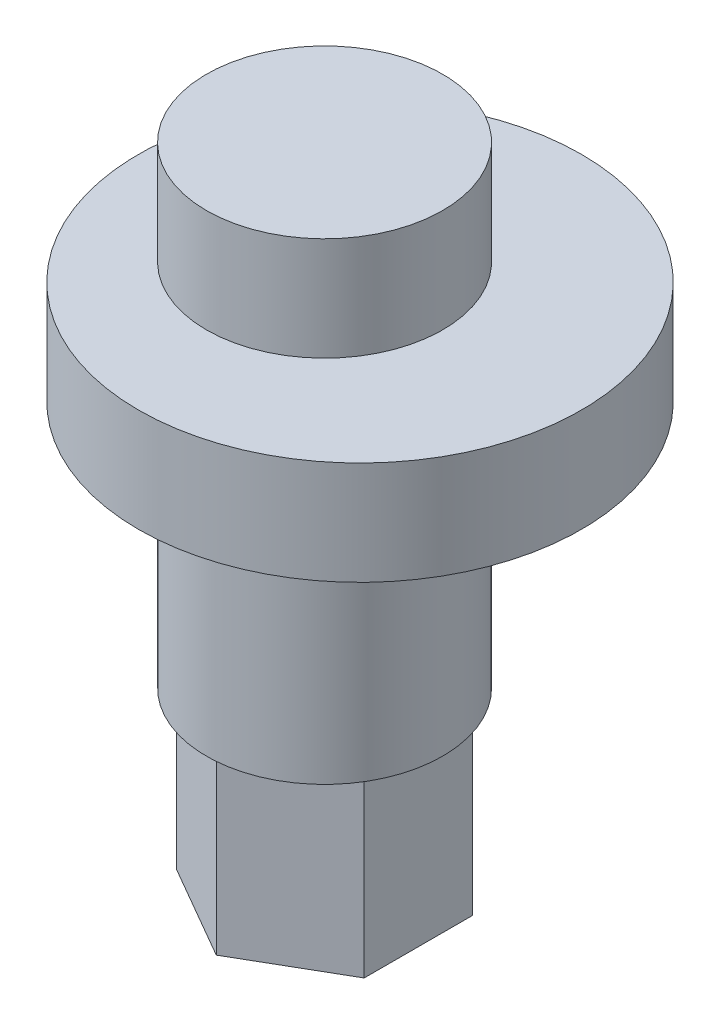
SolidWorks part; units mm, degrees
ref_plane "Front Plane" through (0, 0, 0) normal (0, 0, 1) x (1, 0, 0)
ref_plane "Top Plane" through (0, 0, 0) normal (0, 1, 0) x (1, 0, 0)
ref_plane "Right Plane" through (0, 0, 0) normal (1, 0, 0) x (0, 0, -1)
sketch "Sketch2" plane through (0, 0, 0) normal (0, 1, 0) x (1, 0, 0)
  circle A0 centre (0, 0) radius 4
  circle A1 centre (1.2, 0) radius 7.5
  dimension "D1" = 8
  dimension "D2" = 15
  dimension "D3" = 1.2
sketch "Sketch3" plane through (0, 0, 0) normal (0, 1, 0) x (1, 0, 0)
  circle A0 centre (1.2, 0) radius 7.5 construction
  circle A1 centre (1.2, 0) radius 7.5
extrude "Boss-Extrude1" add sketch "Sketch3" along normal blind 3.5
sketch "Sketch4" plane through (0, 0, 0) normal (0, -1, 0) x (1, 0, 0)
  circle A0 centre (0, 0) radius 4 construction
  circle A1 centre (0, 0) radius 4
extrude "Boss-Extrude2" add sketch "Sketch4" along normal blind 15
sketch "Sketch5" plane through (0, -15, 0) normal (0, -1, 0) x (1, 0, 0)
  line L0 (-15, 0) -> (0, 0) construction
  line L1 (-15, 4) -> (0, 4)
  line L2 (-15, -4) -> (0, -4)
  arc A0 (-15, 4) -> (-15, -4) centre (-15, 0) ccw
  arc A1 (0, -4) -> (0, 4) centre (0, 0) ccw
  circle A2 centre (0, 0) radius 4 construction
  point P3 (-7.5, 0)
  dimension "D1" = 15
extrude "Boss-Extrude3" [suppressed] add sketch "Sketch5" along normal blind 3
sketch "Sketch6" plane through (0, 3.5, 0) normal (0, 1, 0) x (1, 0, 0)
  circle A0 centre (0, 0) radius 4 construction
  circle A1 centre (0, 0) radius 4
extrude "Boss-Extrude4" add sketch "Sketch6" along normal blind 3.5
sketch "Sketch7" plane through (0, -15, 0) normal (0, -1, 0) x (1, 0, 0)
  line L1 (0, 3.6662) -> (-3.175, 1.8331)
  line L2 (-3.175, 1.8331) -> (-3.175, -1.8331)
  line L3 (-3.175, -1.8331) -> (0, -3.6662)
  line L4 (0, -3.6662) -> (3.175, -1.8331)
  line L5 (3.175, -1.8331) -> (3.175, 1.8331)
  line L6 (3.175, 1.8331) -> (0, 3.6662)
  circle A0 centre (0, 0) radius 3.175 construction
  dimension "D1" = 6.35
extrude "Cut-Extrude1" cut sketch "Sketch7" against normal blind 6 flip side to cut
